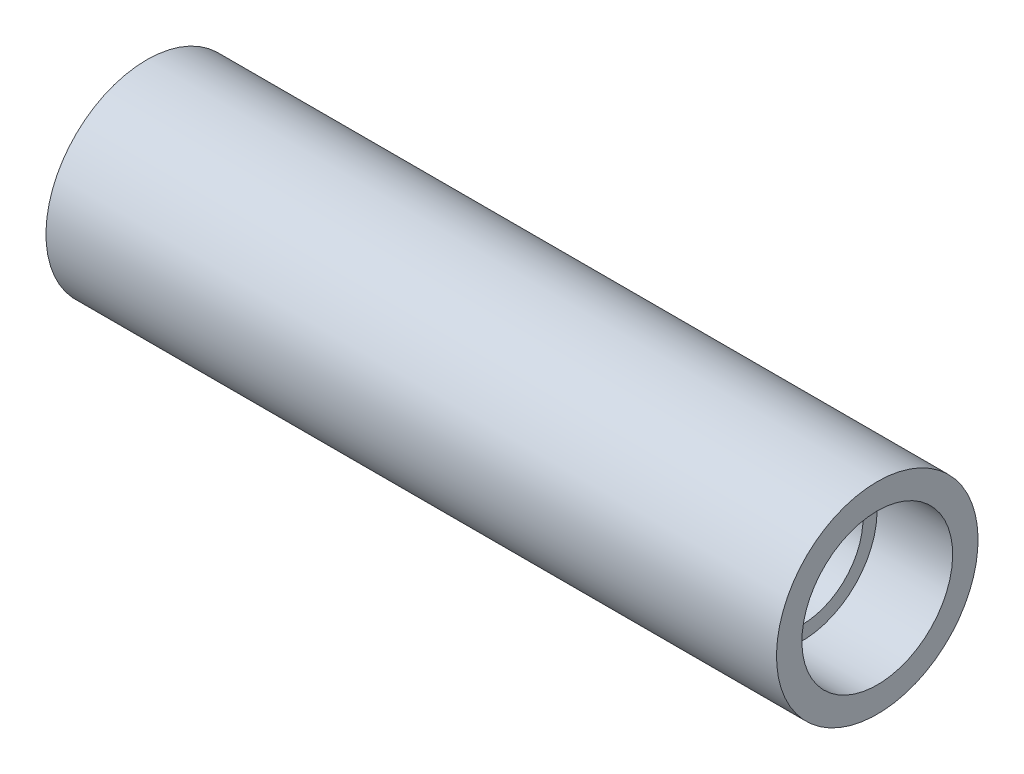
SolidWorks part; units mm, degrees
ref_plane "Front Plane" through (0, 0, 0) normal (0, 0, 1) x (1, 0, 0)
ref_plane "Top Plane" through (0, 0, 0) normal (0, 1, 0) x (1, 0, 0)
ref_plane "Right Plane" through (0, 0, 0) normal (1, 0, 0) x (0, 0, -1)
sketch "Sketch1" plane through (0, 0, 0) normal (0, 0, 1) x (1, 0, 0)
  line L0 (0, 0) -> (23.0188, 0)
  line L1 (23.0188, 0) -> (23.0188, 0.8001)
  line L2 (23.0188, 0.8001) -> (20.6375, 0.8001)
  line L3 (20.6375, 0.8001) -> (20.6375, 3.175)
  line L4 (20.6375, 3.175) -> (2.3812, 3.175)
  line L5 (2.3812, 3.175) -> (2.3813, 0.8001)
  line L6 (2.3813, 0.8001) -> (0, 0.8001)
  line L7 (0, 0.8001) -> (0, 0)
  line L8 (1.6132, 3.175) -> (-5.0451, 3.175) construction
  point P12 (0, 0.4)
  dimension "D1" = 6.35
  dimension "D2" = 4.7498
  dimension "D3" = 2.3813
  dimension "D4" = 23.0188
revolve "Revolve1" add sketch "Sketch1" angle 360 about L8
sketch "Sketch2" plane through (2.3813, 0, 0) normal (-1, 0, 0) x (0, 0, 1)
  circle A0 centre (0, 3.175) radius 2.3749 construction
  point P0 (0, 3.175)
  point P3 (0, 0)
hole_wizard "#24 (0.152) Diameter Hole1" positions "Sketch2" profile "Sketch3" hole size "#24" standard "ANSI Inch" end condition up to next
sketch "Sketch3" plane through (2.3812, 3.175, 0) normal (0, 1, 0) x (0, 0, 1)
  line L0 (0, 0) -> (0, 18.2563)
  line L1 (0, 18.2563) -> (1.9304, 18.2563)
  line L2 (1.9304, 18.2563) -> (1.9304, 0)
  line L5 (1.9304, 0) -> (0, 0)
  line L11 (0, -6.35) -> (0, 107.95) construction
  dimension "Thru Hole Dia." = 3.8608
  dimension "Thru Hole Depth" = 18.2563
